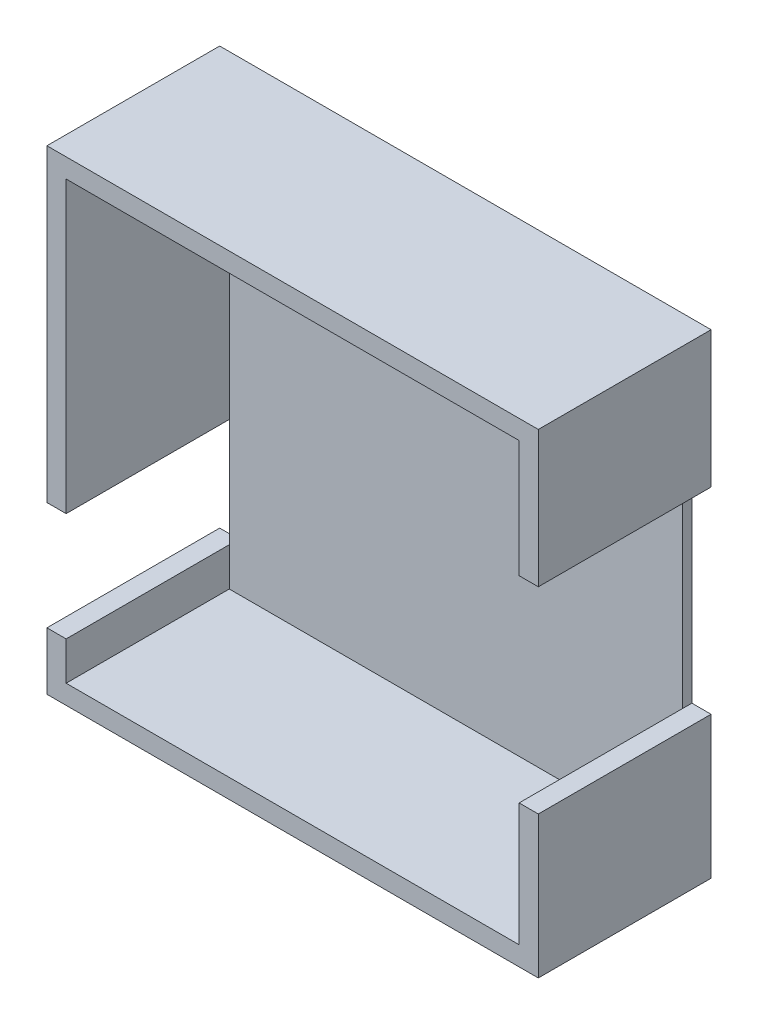
SolidWorks part; units mm, degrees
other "Marquage1"
sketch "Esquisse7" plane through (-25.522, 9.8623, -3) normal (-0.5775, 0.5771, -0.5775) x (-0.7071, 0, 0.7071)
ref_plane "Plan de face" through (0, 0, 0) normal (0, 0, 1) x (1, 0, 0)
ref_plane "Plan de dessus" through (0, 0, 0) normal (0, 1, 0) x (1, 0, 0)
ref_plane "Plan de droite" through (0, 0, 0) normal (1, 0, 0) x (0, 0, -1)
sketch "Esquisse1" plane through (0, 0, 0) normal (0, 0, 1) x (1, 0, 0)
  line L1 (-23.722, -0.1377) -> (23.478, -0.1377)
  line L2 (-23.722, -0.1377) -> (-23.722, -45.6377)
  line L3 (-23.722, -45.6377) -> (23.478, -45.6377)
  line L4 (23.478, -0.1377) -> (23.478, -45.6377)
  line L5 (-25.722, 1.8623) -> (25.478, 1.8623)
  line L6 (-25.722, 1.8623) -> (-25.722, -47.6377)
  line L7 (-25.722, -47.6377) -> (25.478, -47.6377)
  line L8 (25.478, 1.8623) -> (25.478, -47.6377)
  dimension "D1" = 47.2
  dimension "D2" = 45.5
  dimension "D3" = 2
  dimension "D4" = 2
  dimension "D5" = 2
  dimension "D6" = 2
extrude "Boss.-Extru.1" add sketch "Esquisse1" along normal blind 17
sketch "Esquisse2" plane through (25.478, 0, 0) normal (1, 0, 0) x (0, 0, -1)
  line L0 (-17, -47.6377) -> (0, -47.6377) construction
  line L1 (0, 1.8623) -> (1, 1.8623)
  line L2 (0, 1.8623) -> (0, -47.6377)
  line L3 (0, -47.6377) -> (1, -47.6377)
  line L4 (1, 1.8623) -> (1, -47.6377)
  dimension "D1" = 1
  dimension "D2" = 0
extrude "Boss.-Extru.2" add sketch "Esquisse2" against normal blind 51.2
sketch "Esquisse3" plane through (0, 0, 17) normal (0, 0, 1) x (1, 0, 0)
  line L0 (25.478, -47.6377) -> (25.478, 1.8623) construction
  line L1 (25.478, -12.3377) -> (23.478, -12.3377)
  line L2 (25.478, -12.3377) -> (25.478, -32.8377)
  line L3 (25.478, -32.8377) -> (23.478, -32.8377)
  line L4 (23.478, -12.3377) -> (23.478, -32.8377)
  line L6 (-23.722, -0.1377) -> (-23.722, -45.6377) construction
  line L7 (23.478, -0.1377) -> (-23.722, -0.1377) construction
  line L10 (-23.722, -41.6377) -> (-25.722, -41.6377)
  line L11 (-23.722, -41.6377) -> (-23.722, -30.3377)
  line L12 (-23.722, -30.3377) -> (-25.722, -30.3377)
  line L13 (-25.722, -41.6377) -> (-25.722, -30.3377)
  line L14 (-25.722, 1.8623) -> (-25.722, -47.6377) construction
  line L15 (-23.722, -45.6377) -> (23.478, -45.6377) construction
  point P12 (24.478, -12.3377)
  dimension "D1" = 12.2
  dimension "D2" = 12.8
  dimension "D3" = 4
  dimension "D4" = 30.2
  dimension "D5" = 0
extrude "Enlèv. mat.-Extru.2" cut sketch "Esquisse3" against normal blind 19
